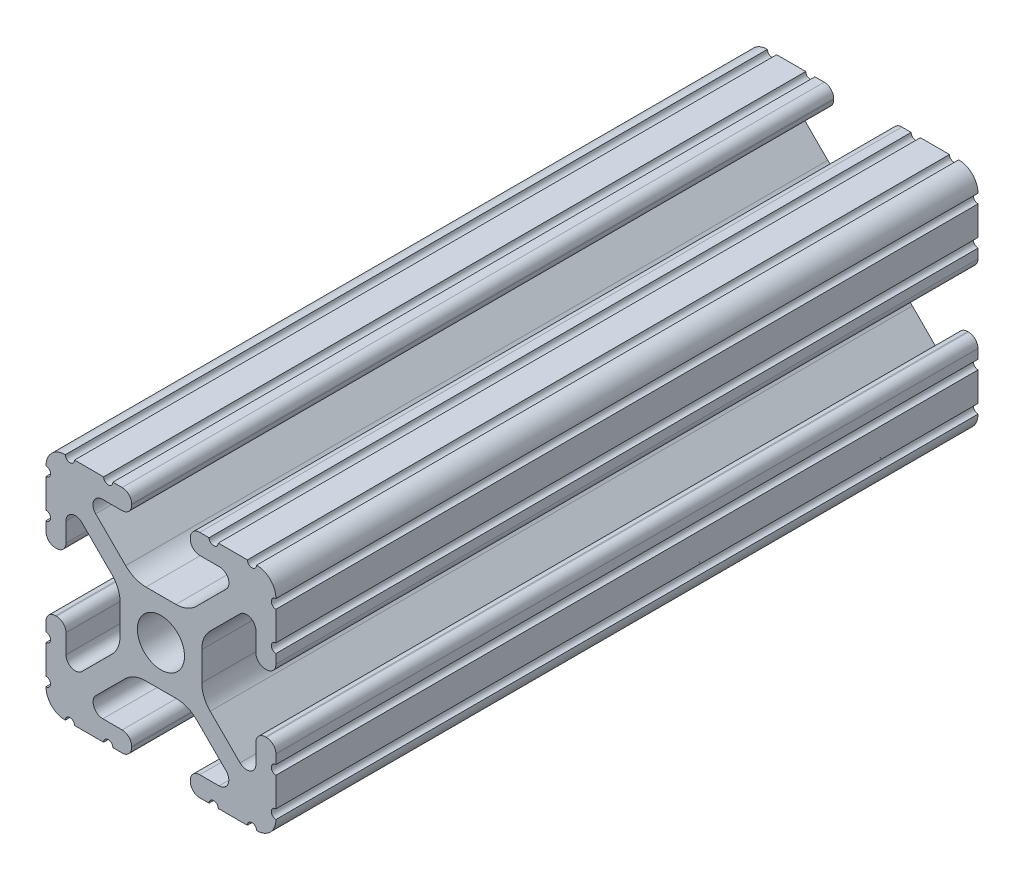
SolidWorks part; units mm, degrees
material "1060 Alloy"
ref_plane "Front Plane" through (0, 0, 0) normal (0, 0, 1) x (1, 0, 0)
ref_plane "Top Plane" through (0, 0, 0) normal (0, 1, 0) x (1, 0, 0)
ref_plane "Right Plane" through (0, 0, 0) normal (1, 0, 0) x (0, 0, -1)
sketch "Sketch1" plane through (0, 0, 0) normal (0, 0, 1) x (1, 0, 0)
  line L88 (-7.1797, -8.6452) -> (-3.9523, -5.4237)
  line L89 (-1.7093, -4.4958) -> (1.7093, -4.4958)
  line L90 (3.9523, -5.4237) -> (7.1797, -8.6452)
  line L91 (6.4164, -10.4902) -> (4.2875, -10.4902)
  line L92 (3.2385, -11.5392) -> (3.2385, -11.651)
  line L93 (4.2875, -12.7) -> (5.3171, -12.7)
  line L94 (6.3331, -12.7) -> (9.5504, -12.7)
  line L95 (12.7, -9.5504) -> (12.7, -6.3331)
  line L96 (12.7, -5.3171) -> (12.7, -4.2875)
  line L97 (11.651, -3.2385) -> (11.5392, -3.2385)
  line L98 (10.4902, -4.2875) -> (10.4902, -6.4021)
  line L99 (8.7371, -7.1294) -> (5.441, -3.8408)
  line L100 (4.5085, -1.5932) -> (4.5085, 1.5932)
  line L101 (5.441, 3.8408) -> (8.7371, 7.1294)
  line L102 (10.4902, 6.4021) -> (10.4902, 4.2875)
  line L103 (11.5392, 3.2385) -> (11.651, 3.2385)
  line L104 (12.7, 4.2875) -> (12.7, 5.3171)
  line L105 (12.7, 6.3331) -> (12.7, 9.5504)
  line L106 (9.5504, 12.7) -> (6.3331, 12.7)
  line L107 (5.3171, 12.7) -> (4.2875, 12.7)
  line L108 (3.2385, 11.651) -> (3.2385, 11.5392)
  line L109 (4.2875, 10.4902) -> (6.4768, 10.4902)
  line L110 (7.207, 8.7244) -> (3.8983, 5.4232)
  line L111 (1.6558, 4.4958) -> (-1.6558, 4.4958)
  line L112 (-3.8983, 5.4232) -> (-7.207, 8.7244)
  line L113 (-6.4768, 10.4902) -> (-4.2875, 10.4902)
  line L114 (-3.2385, 11.5392) -> (-3.2385, 11.651)
  line L115 (-4.2875, 12.7) -> (-5.3171, 12.7)
  line L116 (-6.3331, 12.7) -> (-9.5504, 12.7)
  line L117 (-12.7, 9.5504) -> (-12.7, 6.3331)
  line L118 (-12.7, 5.3171) -> (-12.7, 4.2875)
  line L119 (-11.651, 3.2385) -> (-11.5392, 3.2385)
  line L120 (-10.4902, 4.2875) -> (-10.4902, 6.4021)
  line L121 (-8.7371, 7.1294) -> (-5.441, 3.8408)
  line L122 (-4.5085, 1.5932) -> (-4.5085, -1.5932)
  line L123 (-5.441, -3.8408) -> (-8.7371, -7.1294)
  line L124 (-10.4902, -6.4021) -> (-10.4902, -4.2875)
  line L125 (-11.5392, -3.2385) -> (-11.651, -3.2385)
  line L126 (-12.7, -4.2875) -> (-12.7, -5.3171)
  line L127 (-12.7, -6.3331) -> (-12.7, -9.5504)
  line L128 (-9.5504, -12.7) -> (-6.3331, -12.7)
  line L129 (-5.3171, -12.7) -> (-4.2875, -12.7)
  line L130 (-3.2385, -11.651) -> (-3.2385, -11.5392)
  line L131 (-4.2875, -10.4902) -> (-6.4164, -10.4902)
  circle A1 centre (0, 0) radius 2.6035
  arc A104 (-7.1797, -8.6452) -> (-6.4164, -10.4902) centre (-6.4164, -9.4098) ccw
  arc A105 (-1.7093, -4.4958) -> (-3.9523, -5.4237) centre (-1.7093, -7.6708) ccw
  arc A106 (3.9523, -5.4237) -> (1.7093, -4.4958) centre (1.7093, -7.6708) ccw
  arc A107 (6.4164, -10.4902) -> (7.1797, -8.6452) centre (6.4164, -9.4098) ccw
  arc A108 (4.2875, -10.4902) -> (3.2385, -11.5392) centre (4.2875, -11.5392) ccw
  arc A109 (3.2385, -11.651) -> (4.2875, -12.7) centre (4.2875, -11.651) ccw
  arc A110 (6.3331, -12.7) -> (5.3171, -12.7) centre (5.8251, -12.7) ccw
  arc A111 (10.5664, -12.6998) -> (9.5504, -12.7) centre (10.0584, -12.7) ccw
  arc A112 (10.5664, -12.6998) -> (12.6998, -10.5664) centre (10.5918, -10.5918) ccw
  arc A113 (12.7, -9.5504) -> (12.6998, -10.5664) centre (12.7, -10.0584) ccw
  arc A114 (12.7, -5.3171) -> (12.7, -6.3331) centre (12.7, -5.8251) ccw
  arc A115 (12.7, -4.2875) -> (11.651, -3.2385) centre (11.651, -4.2875) ccw
  arc A116 (11.5392, -3.2385) -> (10.4902, -4.2875) centre (11.5392, -4.2875) ccw
  arc A117 (8.7371, -7.1294) -> (10.4902, -6.4021) centre (9.4628, -6.4021) ccw
  arc A118 (4.5085, -1.5932) -> (5.441, -3.8408) centre (7.6835, -1.5932) ccw
  arc A119 (5.441, 3.8408) -> (4.5085, 1.5932) centre (7.6835, 1.5932) ccw
  arc A120 (10.4902, 6.4021) -> (8.7371, 7.1294) centre (9.4628, 6.4021) ccw
  arc A121 (10.4902, 4.2875) -> (11.5392, 3.2385) centre (11.5392, 4.2875) ccw
  arc A122 (11.651, 3.2385) -> (12.7, 4.2875) centre (11.651, 4.2875) ccw
  arc A123 (12.7, 6.3331) -> (12.7, 5.3171) centre (12.7, 5.8251) ccw
  arc A124 (12.6998, 10.5664) -> (12.7, 9.5504) centre (12.7, 10.0584) ccw
  arc A125 (12.6998, 10.5664) -> (10.5664, 12.6998) centre (10.5918, 10.5918) ccw
  arc A126 (9.5504, 12.7) -> (10.5664, 12.6998) centre (10.0584, 12.7) ccw
  arc A127 (5.3171, 12.7) -> (6.3331, 12.7) centre (5.8251, 12.7) ccw
  arc A128 (4.2875, 12.7) -> (3.2385, 11.651) centre (4.2875, 11.651) ccw
  arc A129 (3.2385, 11.5392) -> (4.2875, 10.4902) centre (4.2875, 11.5392) ccw
  arc A130 (7.207, 8.7244) -> (6.4768, 10.4902) centre (6.4768, 9.4563) ccw
  arc A131 (1.6558, 4.4958) -> (3.8983, 5.4232) centre (1.6558, 7.6708) ccw
  arc A132 (-3.8983, 5.4232) -> (-1.6558, 4.4958) centre (-1.6558, 7.6708) ccw
  arc A133 (-6.4768, 10.4902) -> (-7.207, 8.7244) centre (-6.4768, 9.4563) ccw
  arc A134 (-4.2875, 10.4902) -> (-3.2385, 11.5392) centre (-4.2875, 11.5392) ccw
  arc A135 (-3.2385, 11.651) -> (-4.2875, 12.7) centre (-4.2875, 11.651) ccw
  arc A136 (-6.3331, 12.7) -> (-5.3171, 12.7) centre (-5.8251, 12.7) ccw
  arc A137 (-10.5664, 12.6998) -> (-9.5504, 12.7) centre (-10.0584, 12.7) ccw
  arc A138 (-10.5664, 12.6998) -> (-12.6998, 10.5664) centre (-10.5918, 10.5918) ccw
  arc A139 (-12.7, 9.5504) -> (-12.6998, 10.5664) centre (-12.7, 10.0584) ccw
  arc A140 (-12.7, 5.3171) -> (-12.7, 6.3331) centre (-12.7, 5.8251) ccw
  arc A141 (-12.7, 4.2875) -> (-11.651, 3.2385) centre (-11.651, 4.2875) ccw
  arc A142 (-11.5392, 3.2385) -> (-10.4902, 4.2875) centre (-11.5392, 4.2875) ccw
  arc A143 (-8.7371, 7.1294) -> (-10.4902, 6.4021) centre (-9.4628, 6.4021) ccw
  arc A144 (-4.5085, 1.5932) -> (-5.441, 3.8408) centre (-7.6835, 1.5932) ccw
  arc A145 (-5.441, -3.8408) -> (-4.5085, -1.5932) centre (-7.6835, -1.5932) ccw
  arc A146 (-10.4902, -6.4021) -> (-8.7371, -7.1294) centre (-9.4628, -6.4021) ccw
  arc A147 (-10.4902, -4.2875) -> (-11.5392, -3.2385) centre (-11.5392, -4.2875) ccw
  arc A148 (-11.651, -3.2385) -> (-12.7, -4.2875) centre (-11.651, -4.2875) ccw
  arc A149 (-12.7, -6.3331) -> (-12.7, -5.3171) centre (-12.7, -5.8251) ccw
  arc A150 (-12.6998, -10.5664) -> (-12.7, -9.5504) centre (-12.7, -10.0584) ccw
  arc A151 (-12.6998, -10.5664) -> (-10.5664, -12.6998) centre (-10.5918, -10.5918) ccw
  arc A152 (-9.5504, -12.7) -> (-10.5664, -12.6998) centre (-10.0584, -12.7) ccw
  arc A153 (-5.3171, -12.7) -> (-6.3331, -12.7) centre (-5.8251, -12.7) ccw
  arc A154 (-4.2875, -12.7) -> (-3.2385, -11.651) centre (-4.2875, -11.651) ccw
  arc A155 (-3.2385, -11.5392) -> (-4.2875, -10.4902) centre (-4.2875, -11.5392) ccw
extrude "Boss-Extrude1" add sketch "Sketch1" along normal mid plane 77.5716
